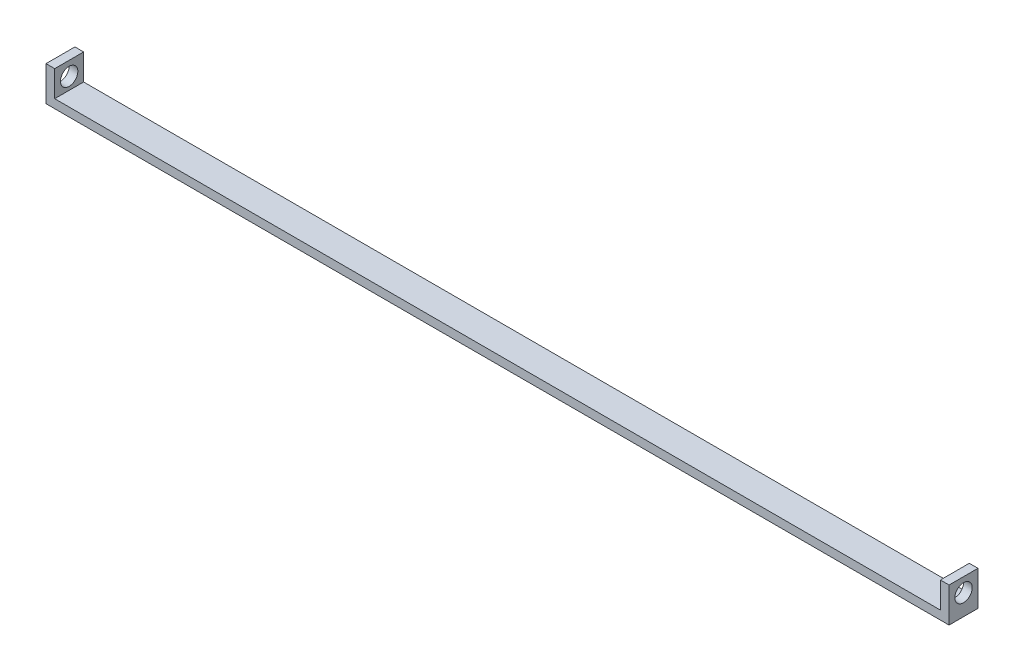
SolidWorks part; units mm, degrees
ref_plane "前视基准面" through (0, 0, 0) normal (0, 0, 1) x (1, 0, 0)
ref_plane "上视基准面" through (0, 0, 0) normal (0, 1, 0) x (1, 0, 0)
ref_plane "右视基准面" through (0, 0, 0) normal (1, 0, 0) x (0, 0, -1)
sketch "草图1" plane through (0, 0, 0) normal (0, 0, 1) x (1, 0, 0)
  line L0 (78, 5.371) -> (76.5, 5.371)
  line L1 (76.5, 0.871) -> (-76.5, 0.871)
  line L2 (78, 0.629) -> (78, -0.629)
  line L3 (78, -0.629) -> (-78, -0.629)
  line L4 (-78, 0.629) -> (-78, -0.629)
  line L5 (0, -0.629) -> (0, 1.5) construction
  line L6 (78, 0) -> (-78, 0) construction
  line L8 (-78, 0.629) -> (-78, 5.371)
  line L9 (-78, 5.371) -> (-76.5, 5.371)
  line L10 (-76.5, 0.871) -> (-76.5, 5.371)
  line L11 (-78, 0.629) -> (-76.5, 5.371) construction
  line L12 (-78, 5.371) -> (-76.5, 0.871) construction
  line L13 (76.5, 0.871) -> (76.5, 5.371)
  line L14 (78, 0.629) -> (78, 5.371)
  point P0 (0, 0)
  point P7 (-77.2304, 3.0621)
  dimension "D1" = 156
  dimension "D2" = 1.5
  dimension "D3" = 6
  dimension "D4" = 1.5
extrude "凸台-拉伸1" add sketch "草图1" along normal blind 5
sketch "草图2" plane through (-78, 0, 0) normal (-1, 0, 0) x (0, 0, 1)
  line L0 (5, 5.371) -> (0, 5.371) construction
  line L2 (5, 5.371) -> (5, -0.629) construction
  circle A0 centre (2.5, 2.971) radius 1.5
  dimension "D1" = 2.4
  dimension "D2" = 2.5
extrude "切除-拉伸1" cut sketch "草图2" against normal blind 318
sketch "草图3" plane through (0, 0, 5) normal (0, 0, 1) x (1, 0, 0)
  line L0 (-76.5, 5.25) -> (-87, 0.871)
  line L1 (-76.5, 0.871) -> (-76.5, 5.371) construction
  line L2 (76.5, 0.871) -> (-76.5, 0.871) construction
  line L3 (-87, 0.871) -> (-87, -0.629)
  line L4 (-78, -0.629) -> (78, -0.629) construction
  line L5 (-87, -0.629) -> (-93, -0.629)
  line L6 (-93, -0.629) -> (-93, 5.25)
  line L7 (-93, 5.25) -> (-76.5, 5.25)
